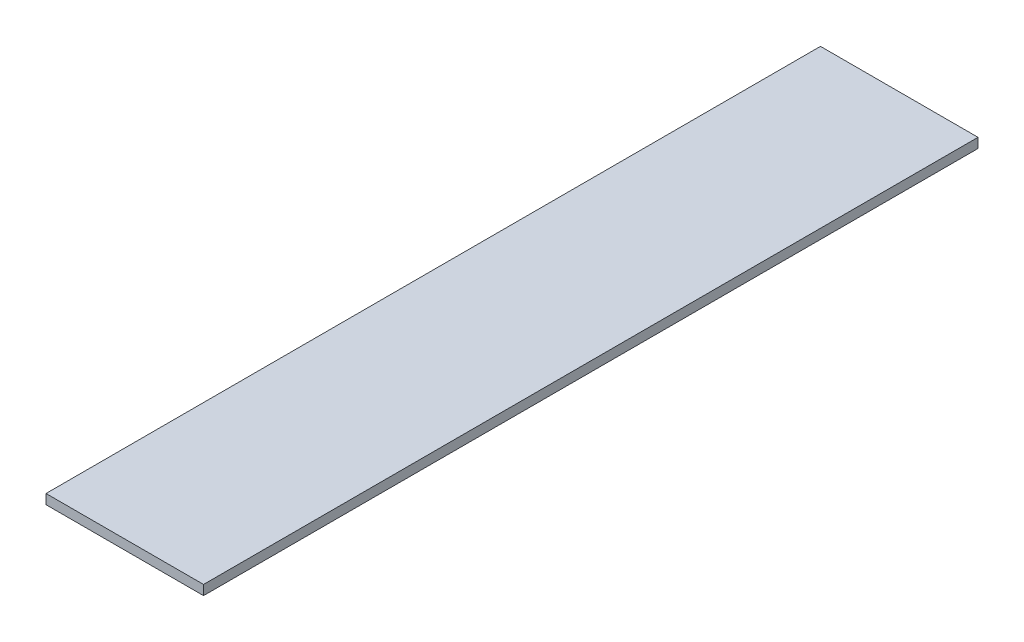
SolidWorks part; units mm, degrees
ref_plane "Front Plane" through (0, 0, 0) normal (0, 0, 1) x (1, 0, 0)
ref_plane "Top Plane" through (0, 0, 0) normal (0, 1, 0) x (1, 0, 0)
ref_plane "Right Plane" through (0, 0, 0) normal (1, 0, 0) x (0, 0, -1)
sketch "Sketch1" plane through (0, 0, 0) normal (0, 0, 1) x (1, 0, 0)
  line L1 (-9.525, -0.5875) -> (9.525, -0.5875)
  line L2 (-9.525, -0.5875) -> (-9.525, 0.5875)
  line L3 (-9.525, 0.5875) -> (9.525, 0.5875)
  line L4 (9.525, -0.5875) -> (9.525, 0.5875)
  line L5 (-9.525, -0.5875) -> (9.525, 0.5875) construction
  line L6 (-9.525, 0.5875) -> (9.525, -0.5875) construction
  point P0 (0, 0)
  dimension "D1" = 1.175
  dimension "D2" = 19.05
extrude "Boss-Extrude1" add sketch "Sketch1" along normal blind 93.65
